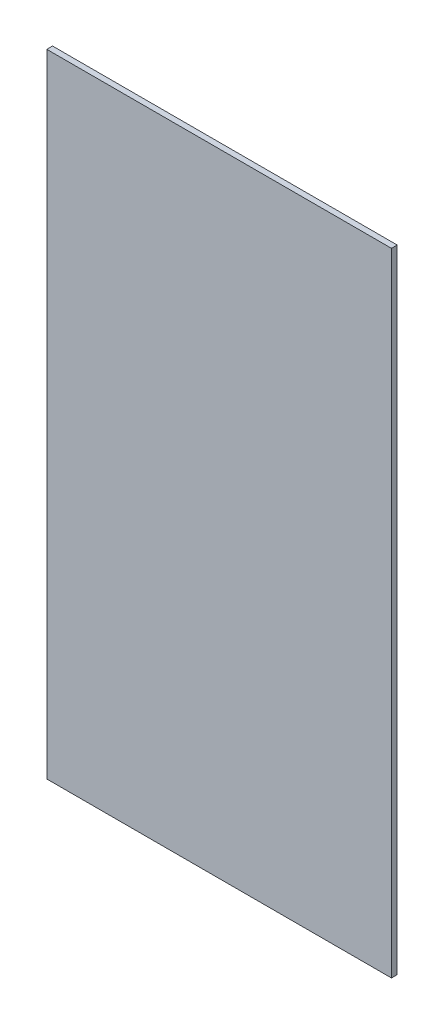
SolidWorks part; units mm, degrees
ref_plane "Front Plane" through (0, 0, 0) normal (0, 0, 1) x (1, 0, 0)
ref_plane "Top Plane" through (0, 0, 0) normal (0, 1, 0) x (1, 0, 0)
ref_plane "Right Plane" through (0, 0, 0) normal (1, 0, 0) x (0, 0, -1)
sketch "Sketch1" plane through (0, 0, 0) normal (0, 0, 1) x (1, 0, 0)
  line L1 (0, 0) -> (60, 0)
  line L2 (0, 0) -> (0, 110)
  line L3 (0, 110) -> (60, 110)
  line L4 (60, 0) -> (60, 110)
  dimension "D1" = 60
  dimension "D2" = 110
extrude "Boss-Extrude1" add sketch "Sketch1" along normal blind 1
